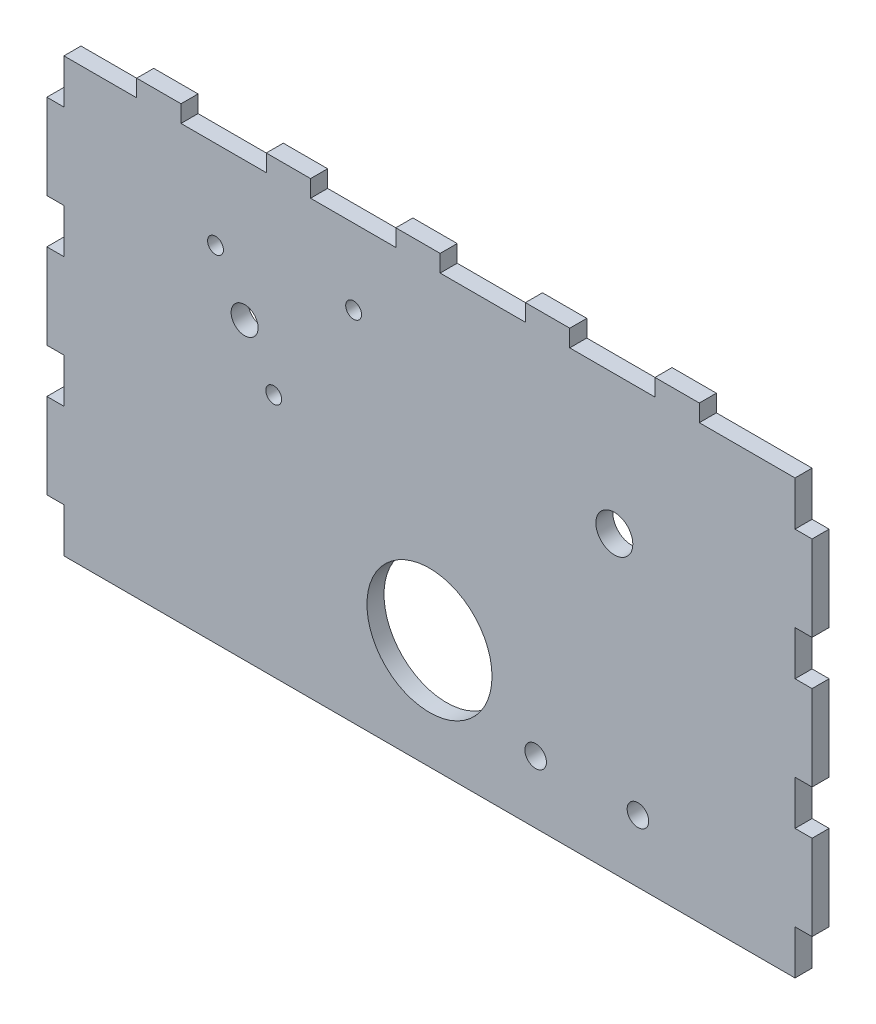
SolidWorks part; units mm, degrees
ref_plane "Front Plane" through (0, 0, 0) normal (0, 0, 1) x (1, 0, 0)
ref_plane "Top Plane" through (0, 0, 0) normal (0, 1, 0) x (1, 0, 0)
ref_plane "Right Plane" through (0, 0, 0) normal (1, 0, 0) x (0, 0, -1)
sketch "Model" plane through (0, 0, 0) normal (0, 0, 1) x (1, 0, 0)
  line L0 (67.32, 30.3) -> (64.32, 30.3)
  line L1 (67.32, 15.3) -> (67.32, 30.3)
  line L2 (64.32, 15.3) -> (67.32, 15.3)
  line L3 (64.32, 7.5) -> (64.32, 15.3)
  line L4 (67.32, 7.5) -> (64.32, 7.5)
  line L5 (67.32, -7.5) -> (67.32, 7.5)
  line L6 (64.32, -7.5) -> (67.32, -7.5)
  line L7 (64.32, -15.3) -> (64.32, -7.5)
  line L8 (67.32, -15.3) -> (64.32, -15.3)
  line L9 (67.32, -30.3) -> (67.32, -15.3)
  line L10 (64.32, -30.3) -> (67.32, -30.3)
  line L11 (64.32, -38.1) -> (64.32, -30.3)
  line L12 (-64.32, -38.1) -> (64.32, -38.1)
  line L13 (-64.32, -38.1) -> (-64.32, -30.3)
  line L14 (-64.32, -30.3) -> (-67.32, -30.3)
  line L15 (-67.32, -15.3) -> (-67.32, -30.3)
  line L16 (-67.32, -15.3) -> (-64.32, -15.3)
  line L17 (-64.32, -15.3) -> (-64.32, -7.5)
  line L18 (-64.32, -7.5) -> (-67.32, -7.5)
  line L19 (-67.32, 7.5) -> (-67.32, -7.5)
  line L20 (-67.32, 7.5) -> (-64.32, 7.5)
  line L21 (-64.32, 7.5) -> (-64.32, 15.3)
  line L22 (-64.32, 15.3) -> (-67.32, 15.3)
  line L23 (-67.32, 30.3) -> (-67.32, 15.3)
  line L24 (-67.32, 30.3) -> (-64.32, 30.3)
  line L25 (-64.32, 30.3) -> (-64.32, 38.1)
  line L26 (-51.52, 38.1) -> (-64.32, 38.1)
  line L27 (-51.52, 41.1) -> (-51.52, 38.1)
  line L28 (-43.72, 41.1) -> (-51.52, 41.1)
  line L29 (-43.72, 41.1) -> (-43.72, 38.1)
  line L30 (-28.72, 38.1) -> (-43.72, 38.1)
  line L31 (-28.72, 41.1) -> (-28.72, 38.1)
  line L32 (-20.92, 41.1) -> (-28.72, 41.1)
  line L33 (-20.92, 41.1) -> (-20.92, 38.1)
  line L34 (-5.92, 38.1) -> (-20.92, 38.1)
  line L35 (-5.92, 41.1) -> (-5.92, 38.1)
  line L36 (1.88, 41.1) -> (-5.92, 41.1)
  line L37 (1.88, 41.1) -> (1.88, 38.1)
  line L38 (16.88, 38.1) -> (1.88, 38.1)
  line L39 (16.88, 41.1) -> (16.88, 38.1)
  line L40 (24.68, 41.1) -> (16.88, 41.1)
  line L41 (24.68, 41.1) -> (24.68, 38.1)
  line L42 (39.68, 38.1) -> (24.68, 38.1)
  line L43 (39.68, 41.1) -> (39.68, 38.1)
  line L44 (47.48, 41.1) -> (39.68, 41.1)
  line L45 (47.48, 41.1) -> (47.48, 38.1)
  line L46 (64.32, 38.1) -> (47.48, 38.1)
  line L47 (64.32, 30.3) -> (64.32, 38.1)
  circle A0 centre (-37.6485, 22.5604) radius 1.397
  circle A1 centre (-27.4053, 4.8935) radius 1.397
  circle A2 centre (-13.3438, 24.8491) radius 1.397
  circle A3 centre (36.68, -27.1) radius 1.8986
  circle A4 centre (18.68, -27.1) radius 1.8986
  circle A5 centre (32.5269, 13.7269) radius 3.25
  circle A6 centre (-32.5269, 13.7269) radius 2.3749
  circle A7 centre (0, -18.8) radius 11
extrude "Boss-Extrude1" add sketch "Model" along normal blind 3
